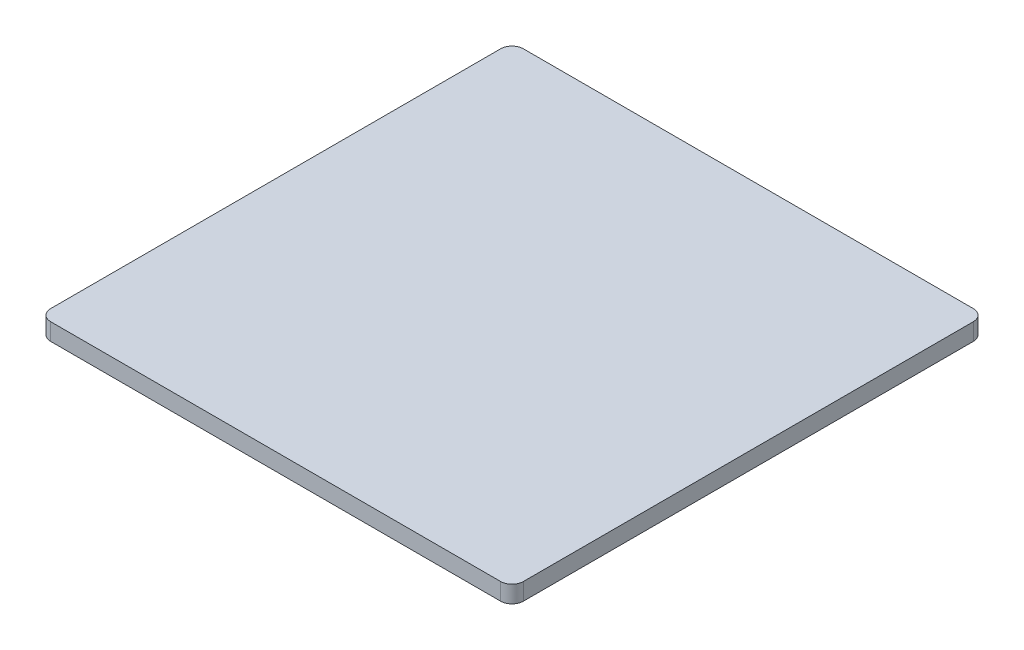
SolidWorks part; units mm, degrees
ref_plane "Front Plane" through (0, 0, 0) normal (0, 0, 1) x (1, 0, 0)
ref_plane "Top Plane" through (0, 0, 0) normal (0, 1, 0) x (1, 0, 0)
ref_plane "Right Plane" through (0, 0, 0) normal (1, 0, 0) x (0, 0, -1)
sketch "Sketch1" plane through (0, 0, 0) normal (0, 1, 0) x (1, 0, 0)
  line L1 (-197.5, 207.5) -> (197.5, 207.5)
  line L2 (-207.5, 197.5) -> (-207.5, -197.5)
  line L3 (-197.5, -207.5) -> (197.5, -207.5)
  line L4 (207.5, 197.5) -> (207.5, -197.5)
  line L5 (-207.5, 207.5) -> (207.5, -207.5) construction
  line L6 (-207.5, -207.5) -> (207.5, 207.5) construction
  arc A0 (-197.5, 207.5) -> (-207.5, 197.5) centre (-197.5, 197.5) ccw
  arc A1 (-207.5, -197.5) -> (-197.5, -207.5) centre (-197.5, -197.5) ccw
  arc A2 (197.5, -207.5) -> (207.5, -197.5) centre (197.5, -197.5) ccw
  arc A3 (197.5, 207.5) -> (207.5, 197.5) centre (197.5, 197.5) cw
  point P0 (0, 0)
  dimension "D3" = 10
  dimension "D4" = 10
  dimension "D1" = 415
  dimension "D2" = 415
extrude "Boss-Extrude1" add sketch "Sketch1" against normal blind 15
sketch "Sketch2" plane through (0, -15, 0) normal (0, -1, 0) x (1, 0, 0)
  line L1 (-190, -200) -> (190, -200)
  line L2 (-200, -190) -> (-200, 190)
  line L3 (-190, 200) -> (190, 200)
  line L4 (200, -190) -> (200, 190)
  line L5 (-200, -200) -> (-195, -195) construction
  line L6 (-200, 200) -> (-195, 195) construction
  line L12 (-175, -195) -> (175, -195)
  line L13 (-200, -190) -> (-190, -200)
  line L14 (-200, 190) -> (-190, 200)
  line L17 (190, 200) -> (200, 190)
  line L19 (190, -200) -> (200, -190)
  line L20 (195, 195) -> (200, 200) construction
  line L21 (195, -195) -> (200, -200) construction
  line L22 (-195, -175) -> (-195, 175)
  line L23 (-175, 195) -> (175, 195)
  line L24 (195, -175) -> (195, 175)
  line L25 (-195, -195) -> (195, 195) construction
  line L26 (-195, 195) -> (195, -195) construction
  arc A0 (195, -175) -> (175, -195) centre (175, -175) cw
  arc A1 (195, 175) -> (175, 195) centre (175, 175) ccw
  arc A2 (-175, 195) -> (-195, 175) centre (-175, 175) ccw
  arc A3 (-175, -195) -> (-195, -175) centre (-175, -175) cw
  point P0 (0, 0)
  point P6 (0, 0)
  point P11 (0, 0)
  dimension "D5" = 20
  dimension "D1" = 400
  dimension "D2" = 400
  dimension "D3" = 390
  dimension "D4" = 390
extrude "Cut-Extrude1" cut sketch "Sketch2" against normal blind 10.5
chamfer "Chamfer1" distance 10 angle 45 8 edges at (0, -15, 195) (195, -15, 0) (0, -15, -195) (-189.1421, -15, -189.1421) (-195, -15, 0) (-189.1421, -15, 189.1421) (189.1421, -15, 189.1421) (189.1421, -15, -189.1421)
